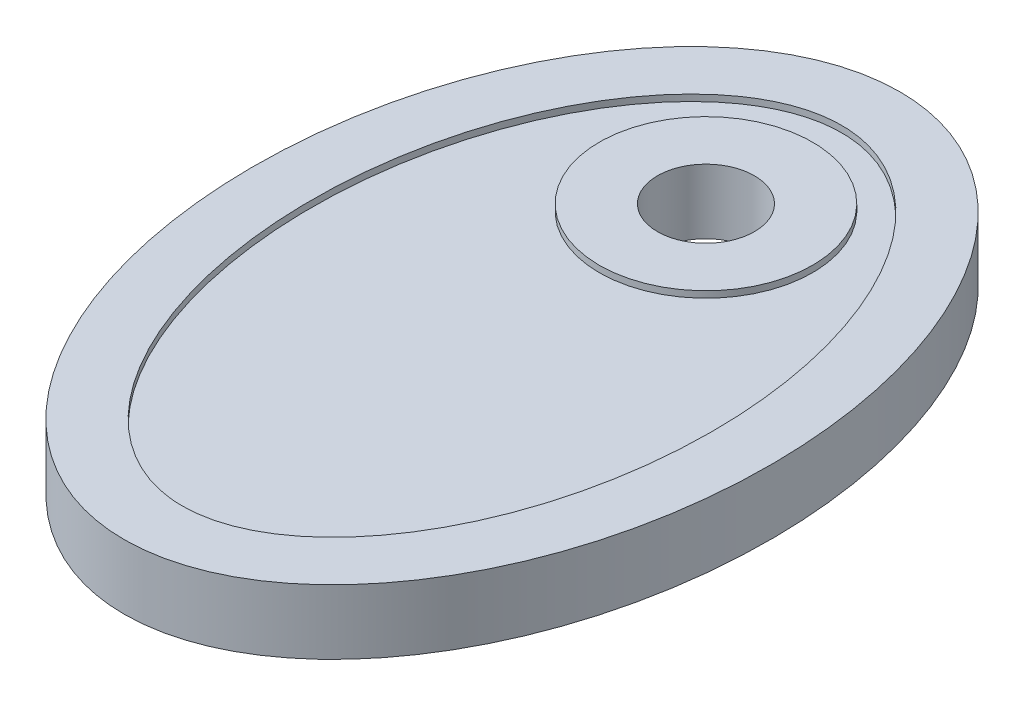
SolidWorks part; units mm, degrees
ref_plane "Front Plane" through (0, 0, 0) normal (0, 0, 1) x (1, 0, 0)
ref_plane "Top Plane" through (0, 0, 0) normal (0, 1, 0) x (1, 0, 0)
ref_plane "Right Plane" through (0, 0, 0) normal (1, 0, 0) x (0, 0, -1)
sketch "Sketch1" plane through (0, 0, 0) normal (0, 1, 0) x (1, 0, 0)
  circle A0 centre (0, 30) radius 7.5
  ellipse E0 centre (0, 0) end of major axis (0, 60) minor radius 40
  ellipse E1 centre (0, 0) end of major axis (0, 55) minor radius 35
  dimension "D7" = 15
  dimension "D1" = 120
  dimension "D2" = 80
  dimension "D3" = 110
  dimension "D4" = 70
  dimension "D5" = 5
  dimension "D6" = 55
  dimension "D8" = 30
  dimension "D9" = 35
extrude "Boss-Extrude1" add sketch "Sketch1" along normal blind 10 contours E1 A0 | E0 E1
shell "Shell5" thickness 9
